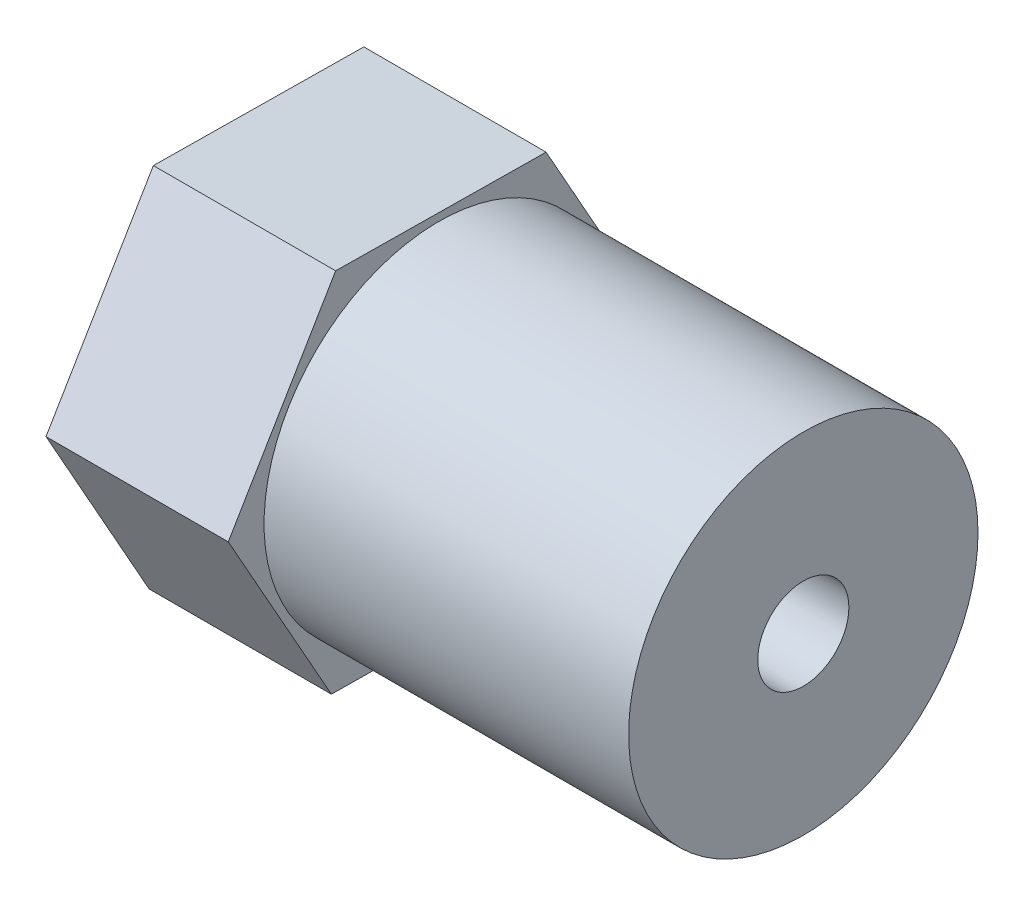
SolidWorks part; units mm, degrees
material "Brass"
ref_plane "Front Plane" through (0, 0, 0) normal (0, 0, 1) x (1, 0, 0)
ref_plane "Top Plane" through (0, 0, 0) normal (0, 1, 0) x (1, 0, 0)
ref_plane "Right Plane" through (0, 0, 0) normal (1, 0, 0) x (0, 0, -1)
sketch "Sketch1" plane through (0, 0, 0) normal (1, 0, 0) x (0, 0, -1)
  line L1 (3.3939, -6.04) -> (6.9277, -0.0808)
  line L2 (6.9277, -0.0808) -> (3.5338, 5.9592)
  line L3 (3.5338, 5.9592) -> (-3.3939, 6.04)
  line L4 (-3.3939, 6.04) -> (-6.9277, 0.0808)
  line L5 (-6.9277, 0.0808) -> (-3.5338, -5.9592)
  line L6 (-3.5338, -5.9592) -> (3.3939, -6.04)
  circle A0 centre (0, 0) radius 6 construction
  dimension "D1" = 12
extrude "Boss-Extrude1" add sketch "Sketch1" along normal blind 6
sketch "Sketch2" plane through (6, 0, 0) normal (1, 0, 0) x (0, 0, -1)
  line L0 (-3.5338, -5.9592) -> (3.5338, 5.9592) construction
  line L1 (-6.9277, 0.0808) -> (6.9277, -0.0808) construction
  circle A0 centre (0, 0) radius 2
  dimension "D1" = 4
extrude "Cut-Extrude1" cut sketch "Sketch2" against normal blind 6
sketch "Sketch3" plane through (6, 0, 0) normal (1, 0, 0) x (0, 0, -1)
  circle A0 centre (0, 0) radius 1.5
  circle A1 centre (0, 0) radius 5.75
  dimension "D1" = 3
  dimension "D2" = 11.5
extrude "Boss-Extrude2" add sketch "Sketch3" along normal blind 12
